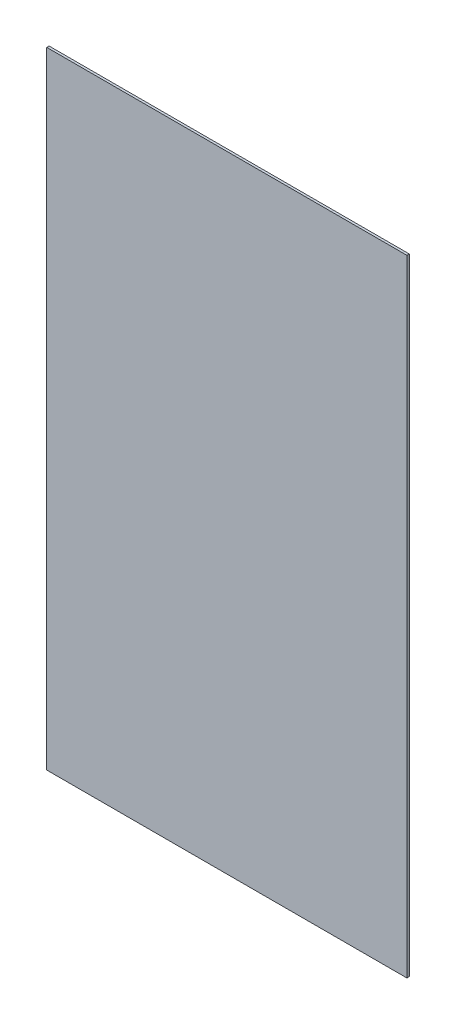
SolidWorks part; units mm, degrees
ref_plane "Front Plane" through (0, 0, 0) normal (0, 0, 1) x (1, 0, 0)
ref_plane "Top Plane" through (0, 0, 0) normal (0, 1, 0) x (1, 0, 0)
ref_plane "Right Plane" through (0, 0, 0) normal (1, 0, 0) x (0, 0, -1)
sketch "Sketch1" plane through (0, 0, 0) normal (0, 0, 1) x (1, 0, 0)
  line L1 (-187.9018, 191.9866) -> (117.0982, 191.9866)
  line L2 (-187.9018, 191.9866) -> (-187.9018, -338.0134)
  line L3 (-187.9018, -338.0134) -> (117.0982, -338.0134)
  line L4 (117.0982, 191.9866) -> (117.0982, -338.0134)
  dimension "D1" = 305
  dimension "D2" = 530
extrude "Boss-Extrude1" add sketch "Sketch1" along normal blind 2
